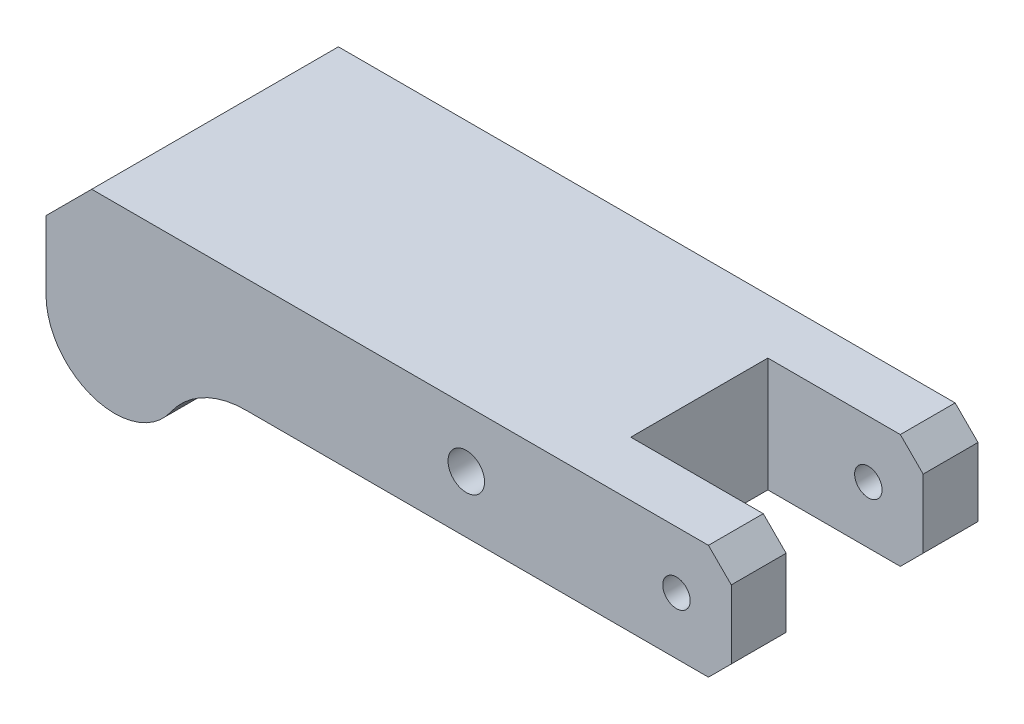
SolidWorks part; units mm, degrees
ref_plane "Front Plane" through (0, 0, 0) normal (0, 0, 1) x (1, 0, 0)
ref_plane "Top Plane" through (0, 0, 0) normal (0, 1, 0) x (1, 0, 0)
ref_plane "Right Plane" through (0, 0, 0) normal (1, 0, 0) x (0, 0, -1)
sketch "Sketch1" plane through (0, 0, 0) normal (0, 0, 1) x (1, 0, 0)
  line L0 (0, 12.5) -> (150, 12.5) construction
  line L1 (43.7228, 0) -> (150, 0)
  line L2 (0, 0) -> (0, 25)
  line L3 (0, 25) -> (150, 25)
  line L4 (150, 0) -> (150, 25)
  arc A0 (0, 0) -> (27.3098, -8.5714) centre (15, 0) ccw
  arc A1 (43.7228, 0) -> (27.3098, -8.5714) centre (43.7228, -20) ccw
  circle A2 centre (92, 12.5) radius 4
  circle A3 centre (138, 12.5) radius 3
  dimension "D4" = 25
  dimension "D3" = 15
  dimension "D5" = 20
  dimension "D6" = 58
  dimension "D7" = 8
  dimension "D8" = 12
  dimension "D9" = 6
  dimension "D1" = 150
  dimension "D2" = 25
extrude "Boss-Extrude1" add sketch "Sketch1" along normal blind 54
chamfer "Chamfer1" distance 5 angle 45 2 edges at (150, 0, 27) (150, 25, 27)
chamfer "Chamfer2" distance 10 angle 45 1 edges at (0, 25, 27)
sketch "Sketch2" plane through (0, 25, 0) normal (0, 1, 0) x (1, 0, 0)
  line L0 (145, -54) -> (145, 0) construction
  line L5 (150, 0) -> (150, -54) construction
  line L11 (150, 0) -> (150, -54)
  line L12 (145, 0) -> (10, 0) construction
  line L13 (150, -42) -> (116, -42)
  line L14 (150, -42) -> (150, -12)
  line L15 (150, -12) -> (116, -12)
  line L16 (116, -42) -> (116, -12)
  point P7 (145, -27)
  line M12 (145, -54) -> (145, 0)
  dimension "D1" = 34
  dimension "D2" = 30
  dimension "D3" = 12
extrude "Cut-Extrude2" cut sketch "Sketch2" against normal through all contours L11 L15 L13 M12 | L16 L13 L15 M12
